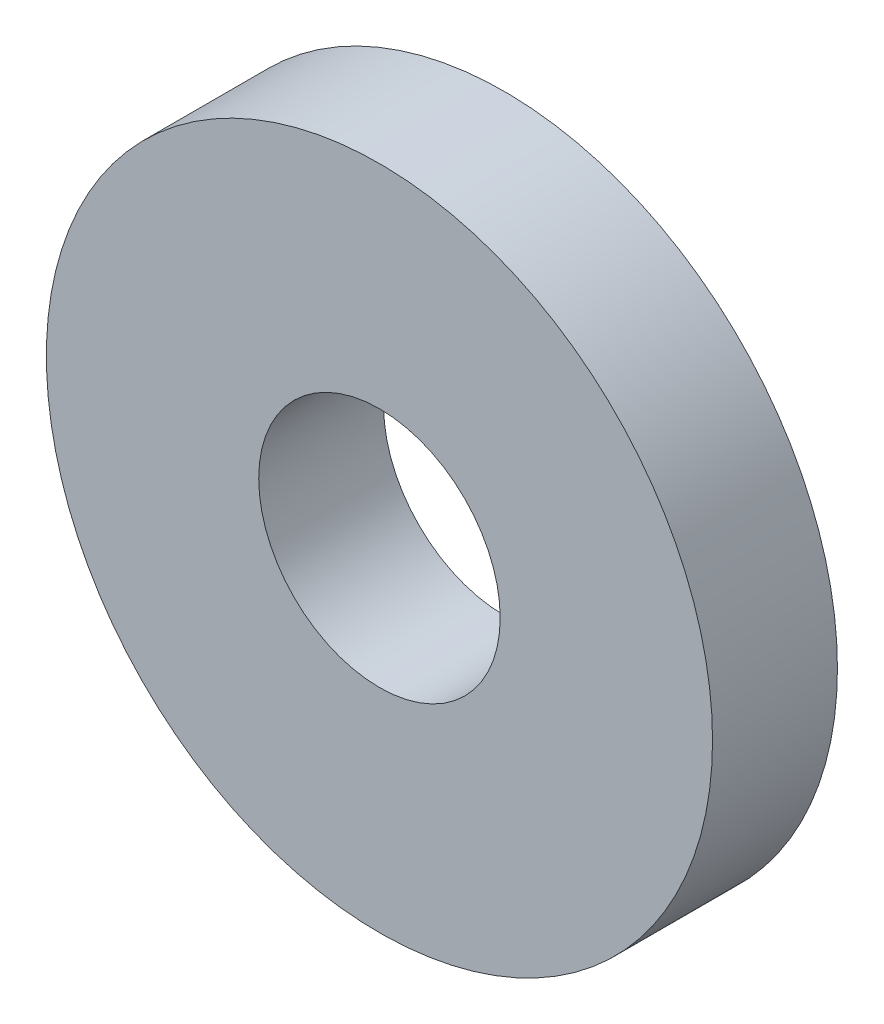
SolidWorks part; units mm, degrees
ref_plane "Front Plane" through (0, 0, 0) normal (0, 0, 1) x (1, 0, 0)
ref_plane "Top Plane" through (0, 0, 0) normal (0, 1, 0) x (1, 0, 0)
ref_plane "Right Plane" through (0, 0, 0) normal (1, 0, 0) x (0, 0, -1)
sketch "Sketch1" plane through (0, 0, 0) normal (0, 0, 1) x (1, 0, 0)
  circle A0 centre (0, 0) radius 4
  circle A1 centre (0, 0) radius 1.45
  dimension "D1" = 2.9
  dimension "D2" = 8
extrude "Boss-Extrude1" add sketch "Sketch1" along normal blind 1.5
